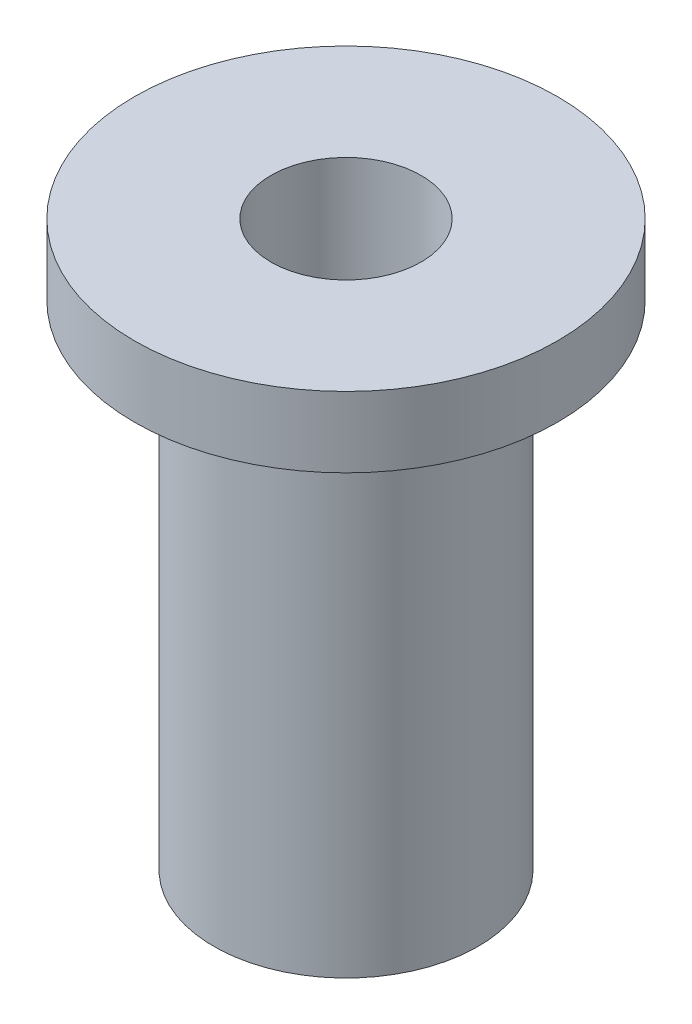
SolidWorks part; units mm, degrees
ref_plane "Front Plane" through (0, 0, 0) normal (0, 0, 1) x (1, 0, 0)
ref_plane "Top Plane" through (0, 0, 0) normal (0, 1, 0) x (1, 0, 0)
ref_plane "Right Plane" through (0, 0, 0) normal (1, 0, 0) x (0, 0, -1)
sketch "Sketch1" plane through (0, 0, 0) normal (0, 0, 1) x (1, 0, 0)
  line L0 (0, 0) -> (0, 353.6557) construction
  line L2 (0, 193.96) -> (2.3813, 193.96)
  line L5 (2.3813, 193.96) -> (2.3813, 202.85)
  line L6 (0, 204.12) -> (3.81, 204.12)
  line L7 (0, 204.12) -> (0, 193.96)
  line L8 (2.3813, 202.85) -> (3.81, 202.85)
  line L9 (3.81, 204.12) -> (3.81, 202.85)
  dimension "D2" = 2.3813
  dimension "D3" = 3.81
  dimension "D4" = 1.27
  dimension "D5" = 8.89
revolve "Revolve1" add sketch "Sketch1" angle 360 about L0
hole_wizard "#6-32 Tapped Hole1" positions "Sketch3" profile "Sketch4" tap size "#6-32" standard "ANSI Inch" end condition through all
sketch "Sketch3" plane through (0, 204.12, 0) normal (0, 1, 0) x (1, 0, 0)
  point P0 (0, 0)
sketch "Sketch4" plane through (0, 204.12, 0) normal (1, 0, 0) x (0, 0, 1)
  line L0 (0, 0) -> (0, 10.16)
  line L1 (0, 10.16) -> (1.3525, 10.16)
  line L2 (1.3525, 10.16) -> (1.3525, 0)
  line L5 (1.3525, 0) -> (0, 0)
  line L11 (0, -6.35) -> (0, 107.95) construction
  dimension "Thru Tap Drill Dia." = 2.7051
  dimension "Thru Tap Drill Depth" = 10.16
cosmetic thread "Hole Thread1" parameters "D2"=3.5052
